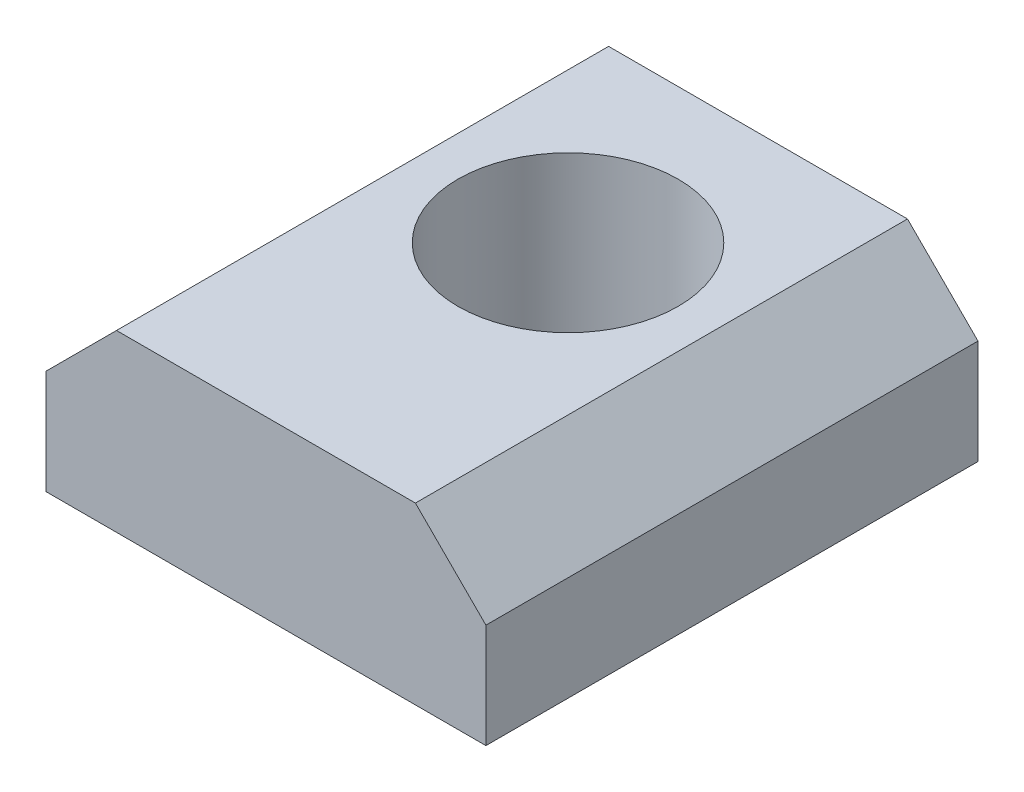
SolidWorks part; units mm, degrees
ref_plane "Front"
ref_plane "Top" through (0, 0, 0) normal (0, 1, 0) x (1, 0, 0)
ref_plane "Right" through (0, 0, 0) normal (1, 0, 0) x (0, 0, -1)
sketch "Sketch1" plane through (0, 0, 0) normal (0, 0, 1) x (1, 0, 0)
  line L1 (0, 0) -> (15.8496, 0)
  line L2 (0, 0) -> (0, 6.2992)
  line L3 (0, 6.2992) -> (15.8496, 6.2992)
  line L4 (15.8496, 0) -> (15.8496, 6.2992)
  dimension "D1" = 15.8496
  dimension "D2" = 6.2992
extrude "Base-Extrude" add sketch "Sketch1" against normal blind 17.7292
hole_wizard "5/16-18 Tapped Hole1" positions "Sketch3" profile "Sketch2" tap size "5/16-18" standard "Ansi Inch"
sketch "Sketch3" plane through (0, 6.2992, 0) normal (0, 1, 0) x (-1, 0, 0)
  line L0 (-15.8496, -17.7292) -> (-15.8496, 0) construction
  line L1 (-15.8496, -17.7292) -> (0, -17.7292) construction
  point P0 (-7.9375, -10.8712)
  dimension "D1" = 7.9121
  dimension "D2" = 6.858
sketch "Sketch2" plane through (7.9375, 6.2992, -10.8712) normal (1, 0, 0) x (0, 0, 1)
  line L0 (0, 0) -> (0, 6.2992)
  line L1 (0, 6.2992) -> (3.2639, 6.2992)
  line L3 (3.2639, 6.2992) -> (3.2639, 15.875)
  line L4 (3.2639, 15.875) -> (3.9687, 15.875)
  line L5 (3.9687, 15.875) -> (3.9687, 0)
  line L7 (3.9687, 0) -> (0, 0)
  line L11 (0, -6.35) -> (0, 107.95) construction
  dimension "Thru Tap Drill Dia." = 6.5278
  dimension "Thru Tap Drill Depth" = 6.2992
  dimension "Thread Dia." = 7.9375
  dimension "Thread Depth" = 15.875
chamfer "Chamfer1" distance 2.54 angle 45
